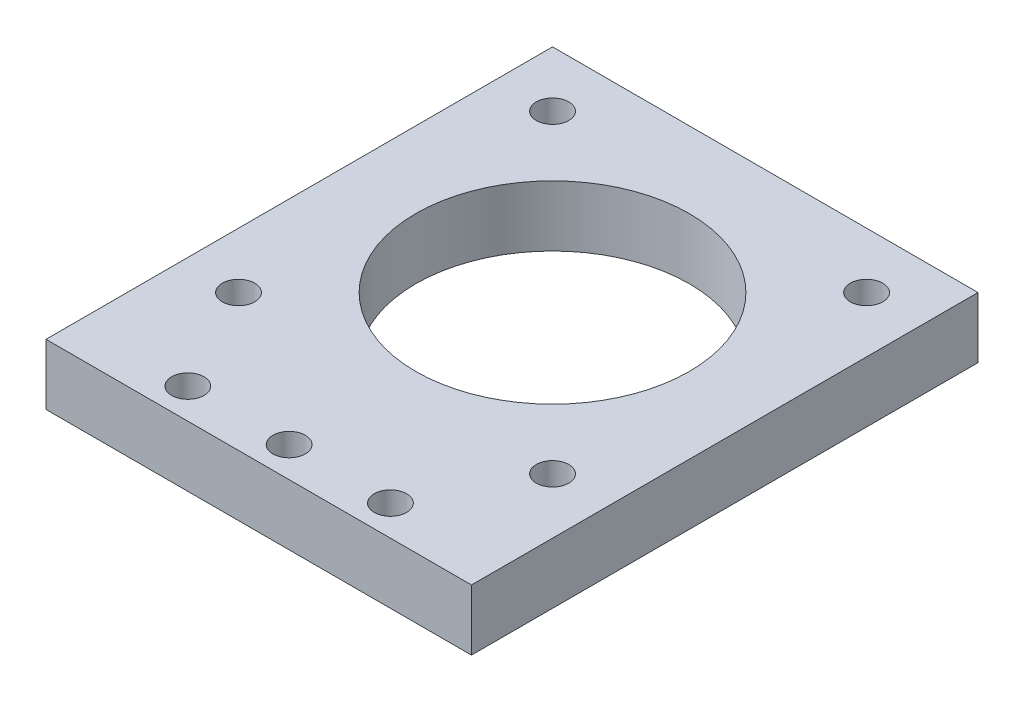
SolidWorks part; units mm, degrees
ref_plane "前视基准面" through (0, 0, 0) normal (0, 0, 1) x (1, 0, 0)
ref_plane "上视基准面" through (0, 0, 0) normal (0, 1, 0) x (1, 0, 0)
ref_plane "右视基准面" through (0, 0, 0) normal (1, 0, 0) x (0, 0, -1)
other "Configuration Table"
sketch "草图1" plane through (0, 0, 0) normal (0, 1, 0) x (1, 0, 0)
  line L0 (21, 50) -> (21, -49950) construction
  line L1 (0, 0) -> (42, 0)
  line L2 (0, 0) -> (0, 50)
  line L3 (0, 50) -> (42, 50)
  line L4 (42, 0) -> (42, 50)
  line L5 (6.9224, 29) -> (50006.9224, 29) construction
  circle A0 centre (21, 3) radius 1.6
  circle A1 centre (5.5, 44.5) radius 1.6
  circle A2 centre (36.5, 44.5) radius 1.6
  circle A5 centre (31, 3) radius 1.6
  circle A6 centre (21, 3) radius 1.6
  circle A7 centre (11, 3) radius 1.6
  circle A9 centre (36.5, 13.5) radius 1.6
  circle A10 centre (5.5, 13.5) radius 1.6
  circle A11 centre (21, 29) radius 13.5
  point P11 (21, 50)
  point P14 (42, 25)
  dimension "D3" = 3.2
  dimension "D4" = 5.5
  dimension "D5" = 3
  dimension "D6" = 3.2
  dimension "D9" = 21
  dimension "D10" = 15.5
  dimension "D11" = 27
  dimension "D1" = 42
  dimension "D2" = 50
  dimension "D7" = 2
  dimension "D8" = 2
extrude "凸台-拉伸1" add sketch "草图1" along normal blind 6 contours L1 L4 L3 L2 A11 A7 A5 A2 A1 A0 A9 A10
